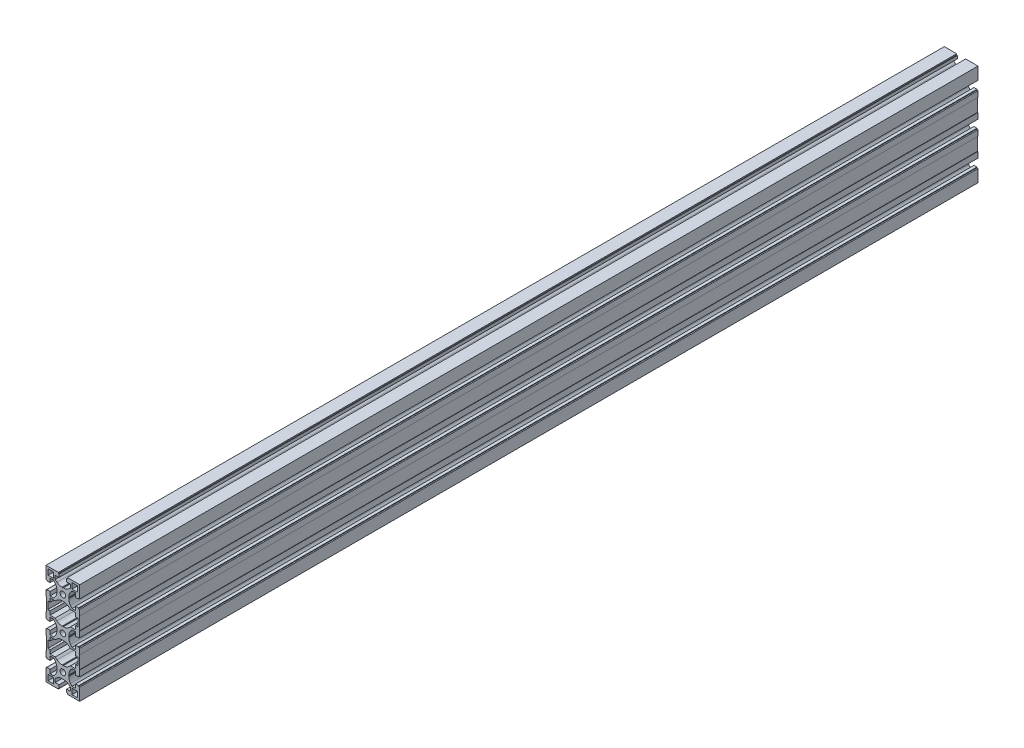
SolidWorks part; units mm, degrees
material "6061 Alloy"
ref_plane "Front Plane" through (0, 0, 0) normal (0, 0, 1) x (1, 0, 0)
ref_plane "Top Plane" through (0, 0, 0) normal (0, 1, 0) x (1, 0, 0)
ref_plane "Right Plane" through (0, 0, 0) normal (1, 0, 0) x (0, 0, -1)
sketch "Model" plane through (0, 0, 0) normal (0, 0, 1) x (1, 0, 0)
  line L0 (-0.5, -8) -> (-1.3008, -8)
  line L1 (-7.8087, -10.4074) -> (-10.25, -12.5)
  line L2 (-10.25, -12.5) -> (-17, -12.5)
  line L3 (-17, -12.5) -> (-17, -17.5)
  line L4 (-17, -17.5) -> (-20, -17.5)
  line L5 (-20, -17.5) -> (-20, -27.5)
  line L6 (-20, -27.5) -> (-17, -27.5)
  line L7 (-17, -27.5) -> (-17, -32.5)
  line L8 (-17, -32.5) -> (-10.25, -32.5)
  line L9 (-10.25, -32.5) -> (-7.8087, -34.5926)
  line L10 (-1.3008, -37) -> (-0.5, -37)
  line L11 (-0.5, -37) -> (0, -37.5)
  line L12 (0, -37.5) -> (0.5, -37)
  line L13 (0.5, -37) -> (1.3008, -37)
  line L14 (7.8087, -34.5926) -> (10.25, -32.5)
  line L15 (10.25, -32.5) -> (17, -32.5)
  line L16 (17, -32.5) -> (17, -27.5)
  line L17 (17, -27.5) -> (20, -27.5)
  line L18 (20, -27.5) -> (20, -17.5)
  line L19 (20, -17.5) -> (17, -17.5)
  line L20 (17, -17.5) -> (17, -12.5)
  line L21 (17, -12.5) -> (10.25, -12.5)
  line L22 (10.25, -12.5) -> (7.8087, -10.4074)
  line L23 (1.3008, -8) -> (0.5, -8)
  line L24 (0.5, -8) -> (0, -7.5)
  line L25 (0, -7.5) -> (-0.5, -8)
  line L26 (0.5, 8) -> (1.3008, 8)
  line L27 (7.8087, 10.4074) -> (10.25, 12.5)
  line L28 (10.25, 12.5) -> (17, 12.5)
  line L29 (17, 12.5) -> (17, 17.5)
  line L30 (17, 17.5) -> (20, 17.5)
  line L31 (20, 17.5) -> (20, 27.5)
  line L32 (20, 27.5) -> (17, 27.5)
  line L33 (17, 27.5) -> (17, 32.5)
  line L34 (17, 32.5) -> (10.25, 32.5)
  line L35 (10.25, 32.5) -> (7.8087, 34.5926)
  line L36 (1.3008, 37) -> (0.5, 37)
  line L37 (0.5, 37) -> (0, 37.5)
  line L38 (0, 37.5) -> (-0.5, 37)
  line L39 (-0.5, 37) -> (-1.3008, 37)
  line L40 (-7.8087, 34.5926) -> (-10.25, 32.5)
  line L41 (-10.25, 32.5) -> (-17, 32.5)
  line L42 (-17, 32.5) -> (-17, 27.5)
  line L43 (-17, 27.5) -> (-20, 27.5)
  line L44 (-20, 27.5) -> (-20, 17.5)
  line L45 (-20, 17.5) -> (-17, 17.5)
  line L46 (-17, 17.5) -> (-17, 12.5)
  line L47 (-17, 12.5) -> (-10.25, 12.5)
  line L48 (-10.25, 12.5) -> (-7.8087, 10.4074)
  line L49 (-1.3008, 8) -> (-0.5, 8)
  line L50 (-0.5, 8) -> (0, 7.5)
  line L51 (0, 7.5) -> (0.5, 8)
  line L52 (19.8, -64.8) -> (19.8, -57.3)
  line L53 (19.8, -57.3) -> (12.3, -57.3)
  line L54 (12.3, -57.3) -> (12.3, -64.8)
  line L55 (12.3, -64.8) -> (19.8, -64.8)
  line L56 (-19.8, -64.8) -> (-12.3, -64.8)
  line L57 (-12.3, -64.8) -> (-12.3, -57.3)
  line L58 (-12.3, -57.3) -> (-19.8, -57.3)
  line L59 (-19.8, -57.3) -> (-19.8, -64.8)
  line L60 (19.8, 64.8) -> (12.3, 64.8)
  line L61 (12.3, 64.8) -> (12.3, 57.3)
  line L62 (12.3, 57.3) -> (19.8, 57.3)
  line L63 (19.8, 57.3) -> (19.8, 64.8)
  line L64 (-19.8, 64.8) -> (-19.8, 57.3)
  line L65 (-19.8, 57.3) -> (-12.3, 57.3)
  line L66 (-12.3, 57.3) -> (-12.3, 64.8)
  line L67 (-12.3, 64.8) -> (-19.8, 64.8)
  line L68 (-12.2299, -10.25) -> (-10.213, -7.7467)
  line L69 (-8, -1.4727) -> (-8, -0.5)
  line L70 (-8, -0.5) -> (-7.5, 0)
  line L71 (-7.5, 0) -> (-8, 0.5)
  line L72 (-8, 0.5) -> (-8, 1.4727)
  line L73 (-10.213, 7.7467) -> (-12.2299, 10.25)
  line L74 (-12.2299, 10.25) -> (-17, 10.25)
  line L75 (-17, 10.25) -> (-17, 5.1)
  line L76 (-17, 5.1) -> (-21, 5.1)
  line L77 (-21, 5.1) -> (-21, 6)
  line L78 (-22.5, 6) -> (-21, 6)
  line L79 (-22.5, 13.75) -> (-22.5, 6)
  line L80 (-22.5, 13.75) -> (-22, 13.75)
  line L81 (-22, 13.75) -> (-22, 31.25)
  line L82 (-22.5, 31.25) -> (-22, 31.25)
  line L83 (-22.5, 39) -> (-22.5, 31.25)
  line L84 (-22.5, 39) -> (-21, 39)
  line L85 (-21, 39) -> (-21, 39.9)
  line L86 (-21, 39.9) -> (-17, 39.9)
  line L87 (-17, 39.9) -> (-17, 34.75)
  line L88 (-17, 34.75) -> (-12.2299, 34.75)
  line L89 (-12.2299, 34.75) -> (-10.213, 37.2533)
  line L90 (-8, 43.5273) -> (-8, 44.5)
  line L91 (-8, 44.5) -> (-7.5, 45)
  line L92 (-7.5, 45) -> (-8, 45.5)
  line L93 (-8, 45.5) -> (-8, 46.4727)
  line L94 (-10.213, 52.7467) -> (-12.2299, 55.25)
  line L95 (-12.2299, 55.25) -> (-17, 55.25)
  line L96 (-17, 55.25) -> (-17, 50.1)
  line L97 (-17, 50.1) -> (-21, 50.1)
  line L98 (-21, 50.1) -> (-21, 51)
  line L99 (-22.5, 51) -> (-21, 51)
  line L100 (-22.5, 67.5) -> (-22.5, 51)
  line L101 (-6, 67.5) -> (-22.5, 67.5)
  line L102 (-6, 67.5) -> (-6, 66)
  line L103 (-6, 66) -> (-5.1, 66)
  line L104 (-5.1, 66) -> (-5.1, 62)
  line L105 (-5.1, 62) -> (-10.25, 62)
  line L106 (-10.25, 62) -> (-10.25, 57.2299)
  line L107 (-10.25, 57.2299) -> (-7.7467, 55.213)
  line L108 (-1.4727, 53) -> (-0.5, 53)
  line L109 (-0.5, 53) -> (0, 52.5)
  line L110 (0, 52.5) -> (0.5, 53)
  line L111 (0.5, 53) -> (1.4727, 53)
  line L112 (7.7467, 55.213) -> (10.25, 57.2299)
  line L113 (10.25, 57.2299) -> (10.25, 62)
  line L114 (10.25, 62) -> (5.1, 62)
  line L115 (5.1, 62) -> (5.1, 66)
  line L116 (5.1, 66) -> (6, 66)
  line L117 (6, 67.5) -> (6, 66)
  line L118 (22.5, 67.5) -> (6, 67.5)
  line L119 (22.5, 51) -> (22.5, 67.5)
  line L120 (22.5, 51) -> (21, 51)
  line L121 (21, 51) -> (21, 50.1)
  line L122 (21, 50.1) -> (17, 50.1)
  line L123 (17, 50.1) -> (17, 55.25)
  line L124 (17, 55.25) -> (12.2299, 55.25)
  line L125 (12.2299, 55.25) -> (10.213, 52.7467)
  line L126 (8, 46.4727) -> (8, 45.5)
  line L127 (8, 45.5) -> (7.5, 45)
  line L128 (7.5, 45) -> (8, 44.5)
  line L129 (8, 44.5) -> (8, 43.5273)
  line L130 (10.213, 37.2533) -> (12.2299, 34.75)
  line L131 (12.2299, 34.75) -> (17, 34.75)
  line L132 (17, 34.75) -> (17, 39.9)
  line L133 (17, 39.9) -> (21, 39.9)
  line L134 (21, 39.9) -> (21, 39)
  line L135 (22.5, 39) -> (21, 39)
  line L136 (22.5, 31.25) -> (22.5, 39)
  line L137 (22.5, 31.25) -> (22, 31.25)
  line L138 (22, 31.25) -> (22, 13.75)
  line L139 (22.5, 13.75) -> (22, 13.75)
  line L140 (22.5, 6) -> (22.5, 13.75)
  line L141 (21, 6) -> (21, 5.1)
  line L142 (21, 5.1) -> (17, 5.1)
  line L143 (17, 5.1) -> (17, 10.25)
  line L144 (17, 10.25) -> (12.2299, 10.25)
  line L145 (12.2299, 10.25) -> (10.213, 7.7467)
  line L146 (8, 1.4727) -> (8, 0.5)
  line L147 (8, 0.5) -> (7.5, 0)
  line L148 (7.5, 0) -> (8, -0.5)
  line L149 (8, -0.5) -> (8, -1.4727)
  line L150 (10.213, -7.7467) -> (12.2299, -10.25)
  line L151 (12.2299, -10.25) -> (17, -10.25)
  line L152 (17, -10.25) -> (17, -5.1)
  line L153 (17, -5.1) -> (21, -5.1)
  line L154 (21, -5.1) -> (21, -6)
  line L155 (22.5, -6) -> (21, -6)
  line L156 (22.5, -13.75) -> (22.5, -6)
  line L157 (22.5, -13.75) -> (22, -13.75)
  line L158 (22, -13.75) -> (22, -31.25)
  line L159 (22.5, -31.25) -> (22, -31.25)
  line L160 (22.5, -39) -> (22.5, -31.25)
  line L161 (22.5, -39) -> (21, -39)
  line L162 (21, -39) -> (21, -39.9)
  line L163 (21, -39.9) -> (17, -39.9)
  line L164 (17, -39.9) -> (17, -34.75)
  line L165 (17, -34.75) -> (12.2299, -34.75)
  line L166 (12.2299, -34.75) -> (10.213, -37.2533)
  line L167 (8, -43.5273) -> (8, -44.5)
  line L168 (8, -44.5) -> (7.5, -45)
  line L169 (7.5, -45) -> (8, -45.5)
  line L170 (8, -45.5) -> (8, -46.4727)
  line L171 (10.213, -52.7467) -> (12.2299, -55.25)
  line L172 (12.2299, -55.25) -> (17, -55.25)
  line L173 (17, -55.25) -> (17, -50.1)
  line L174 (17, -50.1) -> (21, -50.1)
  line L175 (21, -50.1) -> (21, -51)
  line L176 (22.5, -51) -> (21, -51)
  line L177 (22.5, -67.5) -> (22.5, -51)
  line L178 (6, -67.5) -> (22.5, -67.5)
  line L179 (6, -67.5) -> (6, -66)
  line L180 (6, -66) -> (5.1, -66)
  line L181 (5.1, -66) -> (5.1, -62)
  line L182 (5.1, -62) -> (10.25, -62)
  line L183 (10.25, -62) -> (10.25, -57.2299)
  line L184 (10.25, -57.2299) -> (7.7467, -55.213)
  line L185 (1.4727, -53) -> (0.5, -53)
  line L186 (0.5, -53) -> (0, -52.5)
  line L187 (0, -52.5) -> (-0.5, -53)
  line L188 (-0.5, -53) -> (-1.4727, -53)
  line L189 (-7.7467, -55.213) -> (-10.25, -57.2299)
  line L190 (-10.25, -57.2299) -> (-10.25, -62)
  line L191 (-10.25, -62) -> (-5.1, -62)
  line L192 (-5.1, -62) -> (-5.1, -66)
  line L193 (-5.1, -66) -> (-6, -66)
  line L194 (-6, -67.5) -> (-6, -66)
  line L195 (-22.5, -67.5) -> (-6, -67.5)
  line L196 (-22.5, -51) -> (-22.5, -67.5)
  line L197 (-22.5, -51) -> (-21, -51)
  line L198 (-21, -51) -> (-21, -50.1)
  line L199 (-21, -50.1) -> (-17, -50.1)
  line L200 (-17, -50.1) -> (-17, -55.25)
  line L201 (-17, -55.25) -> (-12.2299, -55.25)
  line L202 (-12.2299, -55.25) -> (-10.213, -52.7467)
  line L203 (-8, -46.4727) -> (-8, -45.5)
  line L204 (-8, -45.5) -> (-7.5, -45)
  line L205 (-7.5, -45) -> (-8, -44.5)
  line L206 (-8, -44.5) -> (-8, -43.5273)
  line L207 (-10.213, -37.2533) -> (-12.2299, -34.75)
  line L208 (-12.2299, -34.75) -> (-17, -34.75)
  line L209 (-17, -34.75) -> (-17, -39.9)
  line L210 (-17, -39.9) -> (-21, -39.9)
  line L211 (-21, -39.9) -> (-21, -39)
  line L212 (-22.5, -39) -> (-21, -39)
  line L213 (-22.5, -31.25) -> (-22.5, -39)
  line L214 (-22.5, -31.25) -> (-22, -31.25)
  line L215 (-22, -31.25) -> (-22, -13.75)
  line L216 (-22.5, -13.75) -> (-22, -13.75)
  line L217 (-22.5, -6) -> (-22.5, -13.75)
  line L218 (-22.5, -6) -> (-21, -6)
  line L219 (-21, -6) -> (-21, -5.1)
  line L220 (-21, -5.1) -> (-17, -5.1)
  line L221 (-17, -5.1) -> (-17, -10.25)
  line L222 (-17, -10.25) -> (-12.2299, -10.25)
  line L223 (22.5, 6) -> (21, 6)
  arc A0 (-1.3008, -8) -> (-7.8087, -10.4074) centre (-1.3008, -18) ccw
  arc A1 (-7.8087, -34.5926) -> (-1.3008, -37) centre (-1.3008, -27) ccw
  arc A2 (1.3008, -37) -> (7.8087, -34.5926) centre (1.3008, -27) ccw
  arc A3 (7.8087, -10.4074) -> (1.3008, -8) centre (1.3008, -18) ccw
  arc A4 (1.3008, 8) -> (7.8087, 10.4074) centre (1.3008, 18) ccw
  arc A5 (7.8087, 34.5926) -> (1.3008, 37) centre (1.3008, 27) ccw
  arc A6 (-1.3008, 37) -> (-7.8087, 34.5926) centre (-1.3008, 27) ccw
  arc A7 (-7.8087, 10.4074) -> (-1.3008, 8) centre (-1.3008, 18) ccw
  circle A8 centre (0, -45) radius 3.7
  circle A9 centre (0, 45) radius 3.7
  arc A10 (-10.213, -7.7467) -> (-8, -1.4727) centre (-18, -1.4727) ccw
  arc A11 (-8, 1.4727) -> (-10.213, 7.7467) centre (-18, 1.4727) ccw
  arc A12 (-10.213, 37.2533) -> (-8, 43.5273) centre (-18, 43.5273) ccw
  arc A13 (-8, 46.4727) -> (-10.213, 52.7467) centre (-18, 46.4727) ccw
  arc A14 (-7.7467, 55.213) -> (-1.4727, 53) centre (-1.4727, 63) ccw
  arc A15 (1.4727, 53) -> (7.7467, 55.213) centre (1.4727, 63) ccw
  arc A16 (10.213, 52.7467) -> (8, 46.4727) centre (18, 46.4727) ccw
  arc A17 (8, 43.5273) -> (10.213, 37.2533) centre (18, 43.5273) ccw
  arc A18 (10.213, 7.7467) -> (8, 1.4727) centre (18, 1.4727) ccw
  arc A19 (8, -1.4727) -> (10.213, -7.7467) centre (18, -1.4727) ccw
  arc A20 (10.213, -37.2533) -> (8, -43.5273) centre (18, -43.5273) ccw
  arc A21 (8, -46.4727) -> (10.213, -52.7467) centre (18, -46.4727) ccw
  arc A22 (7.7467, -55.213) -> (1.4727, -53) centre (1.4727, -63) ccw
  arc A23 (-1.4727, -53) -> (-7.7467, -55.213) centre (-1.4727, -63) ccw
  arc A24 (-10.213, -52.7467) -> (-8, -46.4727) centre (-18, -46.4727) ccw
  arc A25 (-8, -43.5273) -> (-10.213, -37.2533) centre (-18, -43.5273) ccw
  circle A26 centre (0, 0) radius 3.7
  dimension "D1" = 7.4
  dimension "D2" = 7.4
  dimension "D3" = 7.4
extrude "Boss-Extrude1" add sketch "Model" against normal blind 1200
equation "\"Lx_Alu_Profile_45x135_Tuli\"= 1200"
equation "\"D1@Boss-Extrude1\"=\"Lx_Alu_Profile_45x135_Tuli\""
